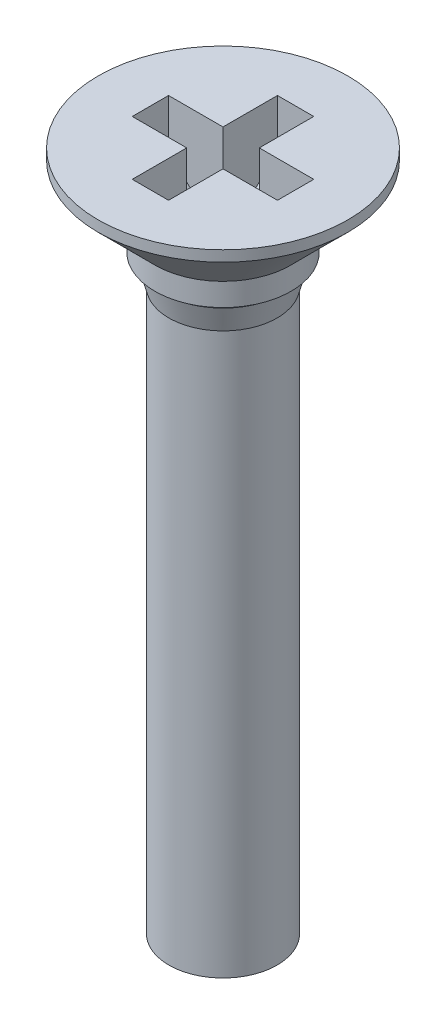
SolidWorks part; units mm, degrees
ref_plane "Vorderseite" through (0, 0, 0) normal (0, 0, 1) x (1, 0, 0)
ref_plane "Oben" through (0, 0, 0) normal (0, 1, 0) x (1, 0, 0)
ref_plane "Rechts" through (0, 0, 0) normal (1, 0, 0) x (0, 0, -1)
sketch "Skizze1" plane through (0, 0, 0) normal (0, 0, 1) x (1, 0, 0)
  line L0 (0, 0) -> (2.75, 0)
  line L1 (2.75, 0) -> (2.75, -0.2375)
  line L2 (2.75, -0.2375) -> (1.5, -1.4875)
  line L3 (1.3375, -1.9875) -> (1.3375, -2.1126)
  line L4 (1.3375, -2.1126) -> (1.1935, -2.65)
  line L5 (1.1935, -2.65) -> (1.1935, -8)
  line L6 (1.1935, -8) -> (0, -8)
  line L7 (0, 0) -> (0, -8) construction
  line L8 (0, 0) -> (0, -8)
  line L10 (1.5, -1.4875) -> (1.5, -1.9875)
  line L12 (1.5, -1.9875) -> (1.3375, -1.9875)
  point P3 (1.3375, -1.65)
  dimension "D1" = 45
  dimension "D2" = 15
  dimension "K" = 1.65
  dimension "DA" = 5.5
  dimension "DK" = 2.387
  dimension "L" = 8
  dimension "DG" = 3
  dimension "A" = 1
  dimension "DF" = 2.675
  dimension "P" = 0.5
revolve "Basis-Rotation" add sketch "Skizze1" angle 360 about L7
sketch "Skizze2" plane through (0, 0, 0) normal (0, 0, 1) x (1, 0, 0)
  line L0 (0, -2.1) -> (0, 0) construction
  line L1 (0, 0) -> (0, -8) construction
  line L2 (-0.55, -2.1) -> (0.55, -2.1)
  line L3 (1.6, 0) -> (1.6, -1.05)
  line L4 (1.6, -1.05) -> (0.55, -2.1)
  line L5 (1.6, 0) -> (-1.6, 0)
  line L6 (-1.6, -1.05) -> (-0.55, -2.1)
  line L7 (-1.6, 0) -> (-1.6, -1.05)
  line L8 (0, -1.05) -> (1.6, -1.05) construction
  line L9 (2.75, 0) -> (-2.75, 0) construction
  line L11 (1.5, -1.4875) -> (2.75, -0.2375) construction
  point P11 (0, 0)
  dimension "M" = 3.2
  dimension "T" = 2.1
extrude "Kreuzschlitz1 H" cut sketch "Skizze2" against normal blind 0.4 and the other way blind 0.4
sketch "Skizze3" plane through (0, 0, 0) normal (1, 0, 0) x (0, 0, -1)
  line L0 (0, -2.1) -> (0, 0) construction
  line L2 (-0.55, -2.1) -> (0.55, -2.1)
  line L3 (1.6, 0) -> (1.6, -1.05)
  line L4 (1.6, -1.05) -> (0.55, -2.1)
  line L5 (1.6, 0) -> (-1.6, 0)
  line L6 (-1.6, -1.05) -> (-0.55, -2.1)
  line L7 (-1.6, 0) -> (-1.6, -1.05)
  line L8 (0, -1.05) -> (1.6, -1.05) construction
  point P11 (0, 0)
extrude "Kreuzschlitz2 H" cut sketch "Skizze3" against normal blind 0.4 and the other way blind 0.4
sketch "Skizze4" plane through (2.4522, 0, -1.8507) normal (0, 1, 0) x (-1, 0, 0)
  line L0 (7.3522, 1.8507) -> (-2.4478, 1.8507) construction
  line L1 (2.4522, -3.0493) -> (2.4522, 6.7507) construction
  line L2 (-2.4478, 1.0342) -> (-2.4478, 2.6672)
  line L3 (-2.4478, 1.0342) -> (0.0059, 1.0342)
  line L4 (0.0059, 1.0342) -> (0.8191, 0.6258)
  line L5 (1.2273, 0.2176) -> (-1.0126, -1.6141)
  line L6 (0.8191, 0.6258) -> (-1.0126, -1.6141)
  line L7 (1.6357, -0.5956) -> (1.2273, 0.2176)
  line L8 (1.6357, -3.0493) -> (1.6357, -0.5956)
  line L9 (1.6357, -3.0493) -> (3.2687, -3.0493)
  line L10 (3.2687, -3.0493) -> (3.2687, -0.5956)
  line L11 (3.2687, -0.5956) -> (3.6772, 0.2176)
  line L12 (2.4522, 1.8507) -> (-1.0126, -1.6141) construction
  line L13 (4.0854, 0.6258) -> (5.917, -1.6141)
  line L14 (3.6772, 0.2176) -> (5.917, -1.6141)
  line L15 (4.8986, 1.0342) -> (4.0854, 0.6258)
  line L16 (7.3522, 1.0342) -> (4.8986, 1.0342)
  line L17 (7.3522, 1.0342) -> (7.3522, 2.6672)
  line L18 (7.3522, 2.6672) -> (4.8986, 2.6672)
  line L19 (4.8986, 2.6672) -> (4.0854, 3.0757)
  line L20 (3.6772, 3.4839) -> (5.917, 5.3156)
  line L21 (4.0854, 3.0757) -> (5.917, 5.3156)
  line L22 (3.2687, 4.2971) -> (3.6772, 3.4839)
  line L23 (3.2687, 6.7507) -> (3.2687, 4.2971)
  line L24 (1.6357, 6.7507) -> (3.2687, 6.7507)
  line L25 (1.6357, 6.7507) -> (1.6357, 4.2971)
  line L26 (1.6357, 4.2971) -> (1.2273, 3.4839)
  line L27 (0.8191, 3.0757) -> (-1.0126, 5.3156)
  line L28 (1.2273, 3.4839) -> (-1.0126, 5.3156)
  line L29 (0.0059, 2.6672) -> (0.8191, 3.0757)
  line L30 (-2.4478, 2.6672) -> (0.0059, 2.6672)
  circle A0 centre (2.4522, 1.8507) radius 4.9 construction
  circle A1 centre (2.4522, 1.8507) radius 2.0415 construction
  circle A2 centre (2.4522, 1.8507) radius 2.579 construction
  dimension "X2" = 4.083
  dimension "X1" = 5.158
  dimension "M" = 9.8
  dimension "D3" = 5.725
  dimension "X3" = 1.633
sketch "Sketch1" plane through (0, -8, 0) normal (0, -1, 0) x (1, 0, 0)
  circle A0 centre (0, 0) radius 1.1935
extrude "Boss-Extrude1" add sketch "Sketch1" along normal blind 7
